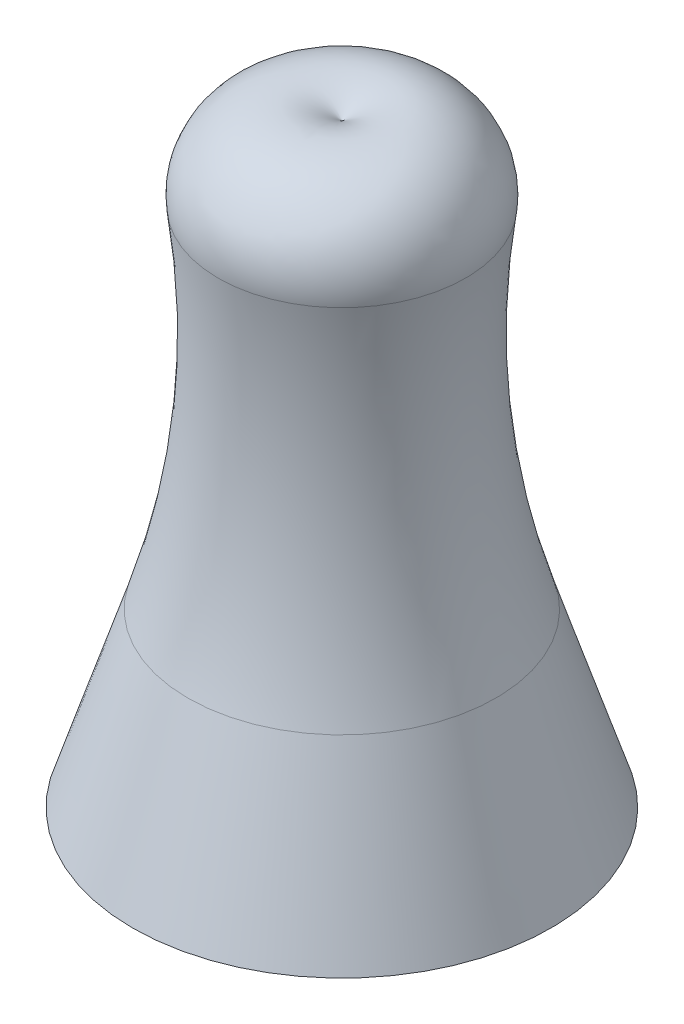
SolidWorks part; units mm, degrees
ref_plane "Front Plane" through (0, 0, 0) normal (0, 0, 1) x (1, 0, 0)
ref_plane "Top Plane" through (0, 0, 0) normal (0, 1, 0) x (1, 0, 0)
ref_plane "Right Plane" through (0, 0, 0) normal (1, 0, 0) x (0, 0, -1)
sketch "Sketch1" plane through (0, 0, 0) normal (0, 0, 1) x (1, 0, 0)
  line L0 (-14.3199, 0) -> (-14.3199, -22.7307)
  line L1 (-6.3199, -22.7307) -> (-8.4316, -16.1719)
  line L4 (-6.3199, -22.7307) -> (-14.3199, -22.7307)
  arc A0 (-14.3199, 0) -> (-9.5889, -2.8432) centre (-12.5603, -2.4298) cw
  arc A1 (-8.4316, -16.1719) -> (-9.5889, -2.8432) centre (20.1248, -6.9777) cw
  dimension "D1" = 30
  dimension "D4" = 8
revolve "Revolve2" add sketch "Sketch1" angle 360 about L0
sketch "Sketch4" plane through (0, -22.7307, 0) normal (0, -1, 0) x (1, 0, 0)
  circle A0 centre (-14.3199, 0) radius 2
extrude "Cut-Extrude3" cut sketch "Sketch4" against normal blind 10 contours A0
